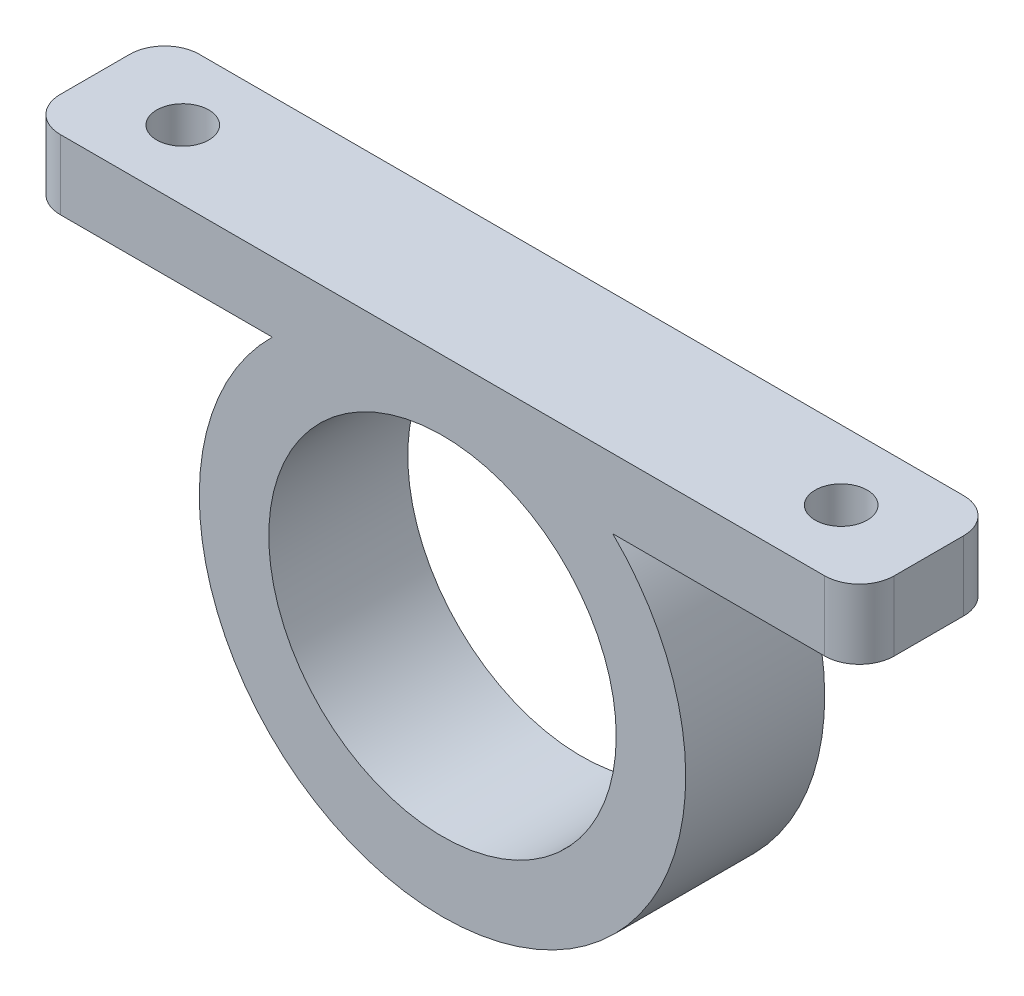
SolidWorks part; units mm, degrees
ref_plane "Alzado" through (0, 0, 0) normal (0, 0, 1) x (1, 0, 0)
ref_plane "Planta" through (0, 0, 0) normal (0, 1, 0) x (1, 0, 0)
ref_plane "Vista lateral" through (0, 0, 0) normal (1, 0, 0) x (0, 0, -1)
sketch "Croquis1" plane through (0, 0, 0) normal (0, 0, 1) x (1, 0, 0)
  line L0 (0, 14) -> (24, 14)
  line L1 (0, 14) -> (-24, 14)
  line L2 (-24, 14) -> (-24, 10)
  line L3 (-24, 10) -> (-9.798, 10)
  line L4 (24, 14) -> (24, 10)
  line L5 (24, 10) -> (9.798, 10)
  circle A0 centre (0, 0) radius 10
  arc A1 (-9.798, 10) -> (9.798, 10) centre (0, 0) ccw
  dimension "D1" = 20
  dimension "D2" = 14
  dimension "D4" = 14
  dimension "D3" = 48
  dimension "D5" = 4
  dimension "D6" = 4
  dimension "D7" = 24
extrude "Saliente-Extruir1" add sketch "Croquis1" along normal blind 8
fillet "Redondeo1" radius 2 4 edges at (24, 12, 8) (24, 12, 0) (-24, 12, 0) (-24, 12, 8)
sketch "Croquis2" plane through (0, 10, 0) normal (0, -1, 0) x (1, 0, 0)
  line L0 (-22, 8) -> (-15.899, 0) construction
  line L1 (-22, 0) -> (-9.798, 0) construction
  line L2 (15.899, 0) -> (22, 8) construction
  line L3 (9.798, 0) -> (22, 0) construction
  circle A0 centre (-18.9495, 4) radius 1.5
  circle A1 centre (18.9495, 4) radius 1.5
  dimension "D1" = 3
  dimension "D2" = 3
extrude "Cortar-Extruir1" cut sketch "Croquis2" against normal through all
